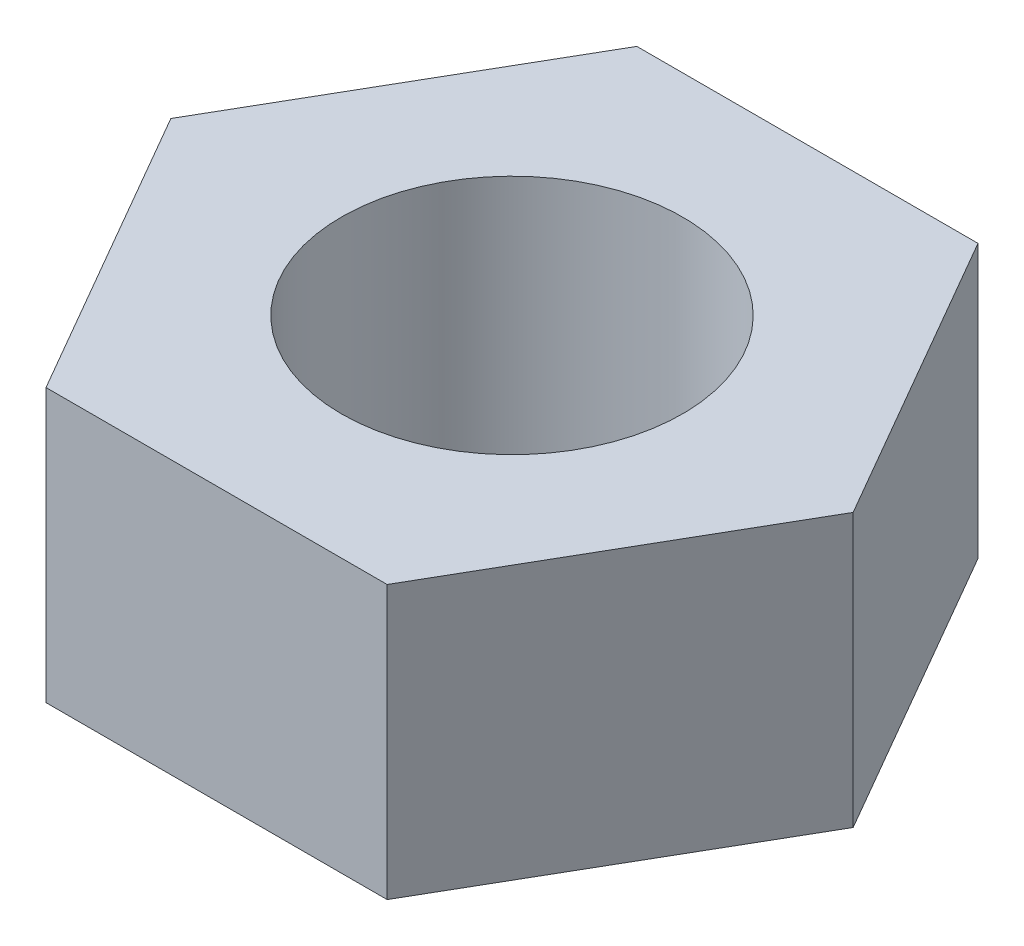
SolidWorks part; units mm, degrees
ref_plane "前视基准面" through (0, 0, 0) normal (0, 0, 1) x (1, 0, 0)
ref_plane "上视基准面" through (0, 0, 0) normal (0, 1, 0) x (1, 0, 0)
ref_plane "右视基准面" through (0, 0, 0) normal (1, 0, 0) x (0, 0, -1)
sketch "草图1" plane through (0, 0, 0) normal (0, 1, 0) x (1, 0, 0)
  line L1 (4, 0) -> (2, 3.4641)
  line L2 (2, 3.4641) -> (-2, 3.4641)
  line L3 (-2, 3.4641) -> (-4, 0)
  line L4 (-4, 0) -> (-2, -3.4641)
  line L5 (-2, -3.4641) -> (2, -3.4641)
  line L6 (2, -3.4641) -> (4, 0)
  circle A0 centre (0, 0) radius 2
  circle A1 centre (0, 0) radius 3.4641 construction
  dimension "D1" = 4
  dimension "D2" = 8
extrude "凸台-拉伸1" add sketch "草图1" along normal blind 3.2
